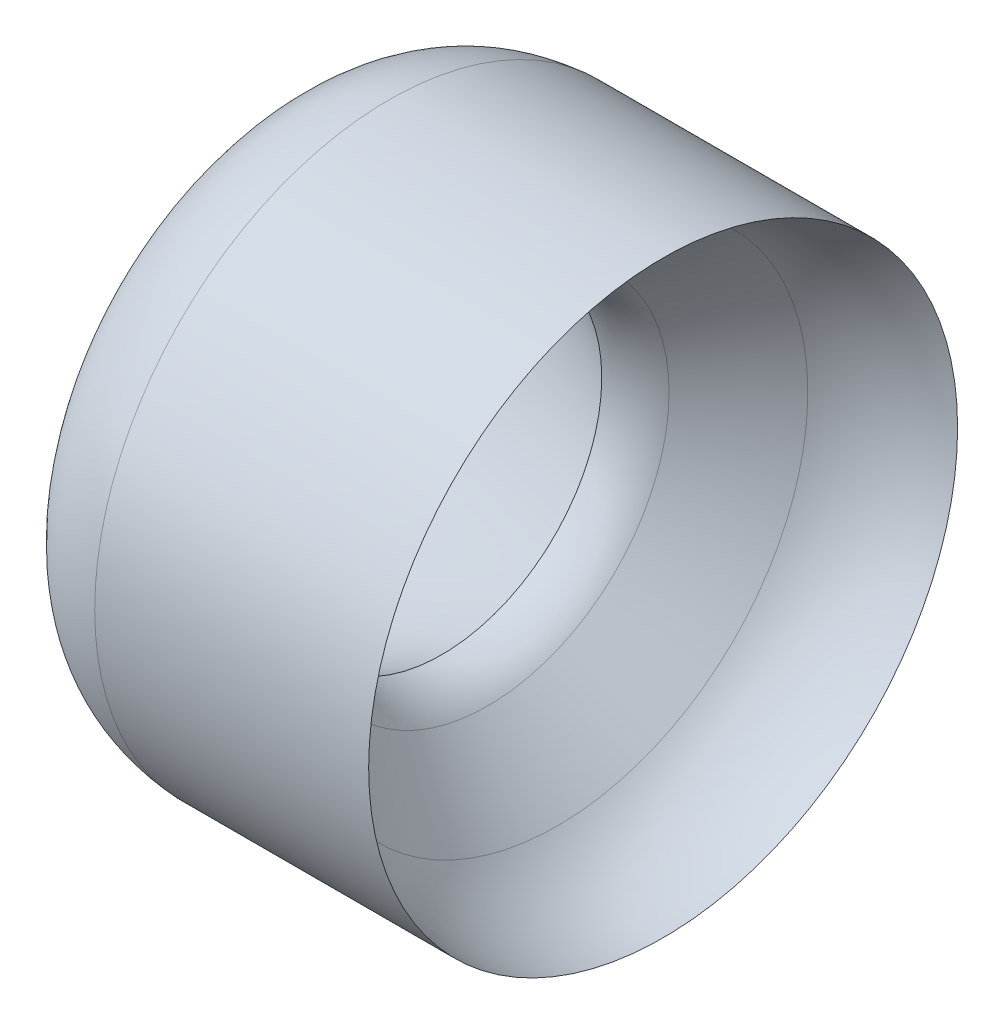
SolidWorks part; units mm, degrees
ref_plane "Front Plane" through (0, 0, 0) normal (0, 0, 1) x (1, 0, 0)
ref_plane "Top Plane" through (0, 0, 0) normal (0, 1, 0) x (1, 0, 0)
ref_plane "Right Plane" through (0, 0, 0) normal (1, 0, 0) x (0, 0, -1)
sketch "Sketch1" plane through (0, 0, 0) normal (0, 0, 1) x (1, 0, 0)
  line L0 (16.2213, 30.1139) -> (7.8848, 21.7775) construction
  line L1 (16.2213, 30.1139) -> (7.8848, 21.7775)
  line L2 (28.9492, 35.386) -> (-3.9696, 35.386)
  line L3 (-206.1482, 0) -> (361.3816, 0) construction
  line L4 (200000, 0) -> (-200234.9488, 0) construction
  arc A0 (28.9492, 35.386) -> (16.2213, 30.1139) centre (28.9492, 17.386) ccw construction
  arc A1 (2.3482, 19.2268) -> (7.8848, 21.7775) centre (1.6623, 28) ccw construction
  arc A2 (28.9492, 35.386) -> (16.2213, 30.1139) centre (28.9492, 17.386) ccw
  arc A3 (2.3482, 19.2268) -> (7.8848, 21.7775) centre (1.6623, 28) ccw
  parabola Q0 (2.3482, 19.2268) -> (-38.315, 32.4321) focus (-82.0238, -79.3988) apex (-72.0854, 37.7774) construction
  parabola Q1 (2.3482, 19.2268) -> (-16.9675, 26.4407) focus (-82.0238, -79.3988) apex (-72.0854, 37.7774)
  spline S0 degree 2 poles (-3.9696, 35.386) (-13.7607, 34.6246) (-16.9675, 26.4407) knots 0 0 0 1 1 1
revolve "Revolve1" add sketch "Sketch1" angle 360 about L3
